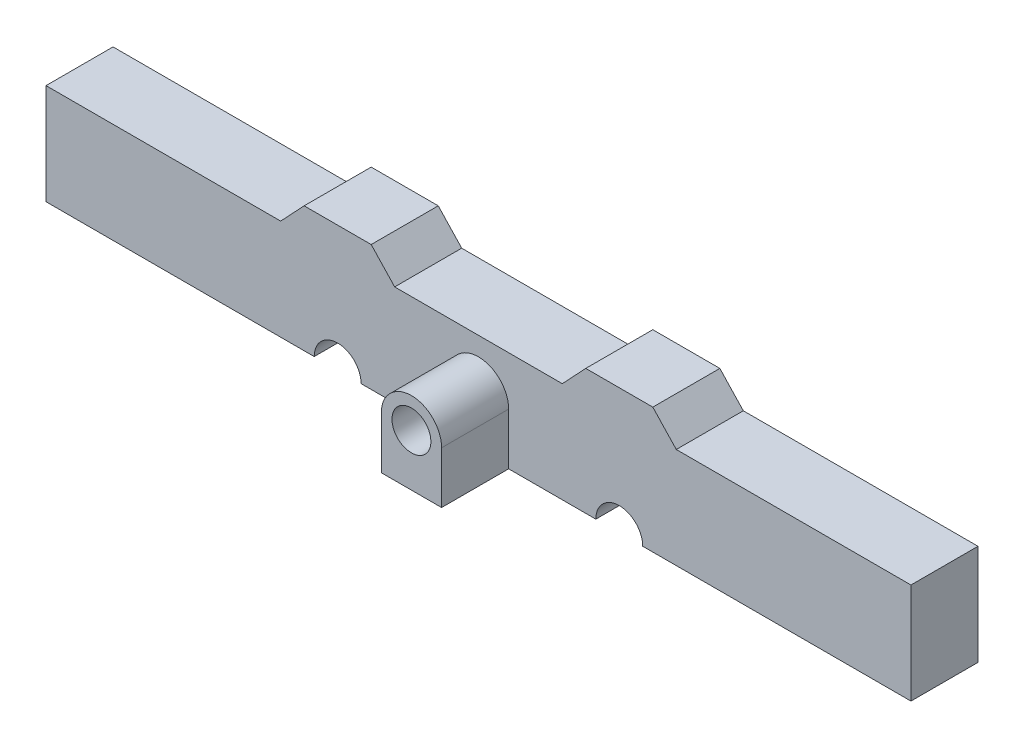
SolidWorks part; units mm, degrees
ref_plane "Front" through (0, 0, 0) normal (0, 0, 1) x (1, 0, 0)
ref_plane "Top" through (0, 0, 0) normal (0, 1, 0) x (1, 0, 0)
ref_plane "Right" through (0, 0, 0) normal (1, 0, 0) x (0, 0, -1)
sketch "Sketch1" plane through (0, 0, 0) normal (0, 0, 1) x (1, 0, 0)
  line L0 (0, 0) -> (0, 15)
  line L1 (0, 15) -> (35, 15)
  line L2 (0, 0) -> (40, 0)
  line L3 (47, 0) -> (82, 0)
  line L4 (43.5, 0) -> (43.5, 49.0227) construction
  line L5 (35, 15) -> (38.5, 18.7242)
  line L6 (38.5, 18.7242) -> (48.5, 18.7242)
  line L7 (52, 15) -> (48.5, 18.7242)
  line L8 (80.5, 18.7238) -> (77.0007, 15)
  line L9 (85.5, -4.9161) -> (85.5, 29.3767) construction
  line L10 (52, 15) -> (52, 49.0227) construction
  line L11 (52, 49.0227) -> (52, -10.3312) construction
  line L12 (77.0007, 15) -> (52, 15)
  line L13 (80.5, 18.7238) -> (85.5, 18.7238)
  line L14 (90.5, 18.7238) -> (85.5, 18.7238)
  line L15 (90.5, 18.7238) -> (93.9993, 15)
  line L16 (89, 0) -> (129, 0)
  line L17 (129, 0) -> (129, 15)
  line L18 (129, 15) -> (93.9993, 15)
  line L19 (2, 13) -> (35.865, 13)
  line L20 (35.865, 13) -> (39.365, 16.7242)
  line L21 (39.365, 16.7242) -> (47.635, 16.7242)
  line L22 (51.135, 13) -> (47.635, 16.7242)
  line L23 (77.8657, 13) -> (51.135, 13)
  line L24 (81.3651, 16.7238) -> (77.8657, 13)
  line L25 (81.3651, 16.7238) -> (85.5, 16.7238)
  line L26 (89.6349, 16.7238) -> (85.5, 16.7238)
  line L27 (89.6349, 16.7238) -> (93.1343, 13)
  line L28 (127, 13) -> (93.1343, 13)
  line L29 (127, 2) -> (127, 13)
  line L30 (90.6235, 2) -> (127, 2)
  line L31 (48.6235, 2) -> (80.3765, 2)
  line L32 (2, 2) -> (38.3765, 2)
  line L33 (2, 2) -> (2, 13)
  arc A0 (40, 0) -> (47, 0) centre (43.5, 0) cw
  arc A1 (82, 0) -> (89, 0) centre (85.5, 0) cw
  arc A2 (80.3765, 2) -> (90.6235, 2) centre (85.5, 0) cw
  arc A3 (38.3765, 2) -> (48.6235, 2) centre (43.5, 0) cw
  point P13 (43.5, 18.7242)
  point P22 (85.5, 13.5903)
  point P25 (85.5, 13.9843)
  dimension "D3" = 3.5
  dimension "D4" = 15
  dimension "D5" = 3.5
  dimension "D1" = 40
  dimension "D2" = 35
  dimension "D6" = 42
  dimension "D7" = 10
  dimension "D8" = 5
  dimension "D9" = 40
  dimension "D11" = 133.22
  dimension "D10" = 133.222
  dimension "D12" = 5.11
  dimension "D13" = 2
extrude "Boss-Extrude1" add sketch "Sketch1" along normal blind 10
sketch "Sketch2" plane through (0, 0, 10) normal (0, 0, 1) x (1, 0, 0)
  line L14 (0, 0) -> (40, 0)
  line L15 (47, 0) -> (82, 0)
  line L16 (89, 0) -> (129, 0)
  line L17 (129, 0) -> (129, 15)
  line L18 (129, 0) -> (129, 15)
  line L19 (129, 15) -> (93.9993, 15)
  line L20 (129, 15) -> (93.9993, 15)
  line L21 (93.9993, 15) -> (90.5, 18.7238)
  line L22 (93.9993, 15) -> (90.5, 18.7238)
  line L23 (52, 15) -> (48.5, 18.7242)
  line L24 (48.5, 18.7242) -> (38.5, 18.7242)
  line L25 (38.5, 18.7242) -> (35, 15)
  line L26 (35, 15) -> (0, 15)
  line L27 (0, 15) -> (0, 0)
  line L28 (0, 0) -> (40, 0)
  line L29 (47, 0) -> (82, 0)
  line L30 (89, 0) -> (129, 0)
  line L31 (90.5, 18.7238) -> (80.5, 18.7238)
  line L32 (90.5, 18.7238) -> (80.5, 18.7238)
  line L33 (80.5, 18.7238) -> (77.0007, 15)
  line L34 (80.5, 18.7238) -> (77.0007, 15)
  line L35 (77.0007, 15) -> (52, 15)
  line L36 (77.0007, 15) -> (52, 15)
  line L37 (52, 15) -> (48.5, 18.7242)
  line L38 (48.5, 18.7242) -> (38.5, 18.7242)
  line L39 (38.5, 18.7242) -> (35, 15)
  line L40 (35, 15) -> (0, 15)
  line L41 (0, 15) -> (0, 0)
  arc A2 (47, 0) -> (40, 0) centre (43.5, 0) ccw
  arc A3 (89, 0) -> (82, 0) centre (85.5, 0) ccw
  arc A4 (47, 0) -> (40, 0) centre (43.5, 0) ccw
  arc A5 (89, 0) -> (82, 0) centre (85.5, 0) ccw
  dimension "D1" = 0
extrude "Boss-Extrude2" add sketch "Sketch2" against normal blind 2
sketch "Sketch3" plane through (0, 0, 0) normal (0, 0, -1) x (-1, 0, 0)
  line L14 (-40, 0) -> (0, 0)
  line L15 (0, 0) -> (0, 15)
  line L16 (0, 15) -> (-35, 15)
  line L17 (-35, 15) -> (-38.5, 18.7242)
  line L18 (-38.5, 18.7242) -> (-48.5, 18.7242)
  line L19 (-48.5, 18.7242) -> (-52, 15)
  line L20 (-52, 15) -> (-77.0007, 15)
  line L21 (-52, 15) -> (-77.0007, 15)
  line L22 (-77.0007, 15) -> (-80.5, 18.7238)
  line L23 (-77.0007, 15) -> (-80.5, 18.7238)
  line L24 (-80.5, 18.7238) -> (-90.5, 18.7238)
  line L25 (-80.5, 18.7238) -> (-90.5, 18.7238)
  line L26 (-129, 0) -> (-89, 0)
  line L27 (-82, 0) -> (-47, 0)
  line L28 (-40, 0) -> (0, 0)
  line L29 (0, 0) -> (0, 15)
  line L30 (0, 15) -> (-35, 15)
  line L31 (-35, 15) -> (-38.5, 18.7242)
  line L32 (-38.5, 18.7242) -> (-48.5, 18.7242)
  line L33 (-48.5, 18.7242) -> (-52, 15)
  line L34 (-90.5, 18.7238) -> (-93.9993, 15)
  line L35 (-90.5, 18.7238) -> (-93.9993, 15)
  line L36 (-93.9993, 15) -> (-129, 15)
  line L37 (-93.9993, 15) -> (-129, 15)
  line L38 (-129, 15) -> (-129, 0)
  line L39 (-129, 15) -> (-129, 0)
  line L40 (-129, 0) -> (-89, 0)
  line L41 (-82, 0) -> (-47, 0)
  arc A2 (-82, 0) -> (-89, 0) centre (-85.5, 0) ccw
  arc A3 (-40, 0) -> (-47, 0) centre (-43.5, 0) ccw
  arc A4 (-82, 0) -> (-89, 0) centre (-85.5, 0) ccw
  arc A5 (-40, 0) -> (-47, 0) centre (-43.5, 0) ccw
  dimension "D1" = 0
extrude "Boss-Extrude3" add sketch "Sketch3" against normal blind 2
sketch "Sketch6" plane through (0, 0, 10) normal (0, 0, 1) x (1, 0, 0)
  circle A0 centre (64.5003, 7.7173) radius 4.5
  circle A1 centre (64.5003, 7.7173) radius 2.9
  dimension "D1" = 5.8
  dimension "D2" = 9
extrude "Boss-Extrude4" add sketch "Sketch6" along normal blind 10
sketch "Sketch7" plane through (0, 0, 10) normal (0, 0, 1) x (1, 0, 0)
  circle A0 centre (64.5003, 7.7173) radius 2.9
extrude "Cut-Extrude1" cut sketch "Sketch7" against normal blind 8
sketch "Sketch9" plane through (0, 0, 10) normal (0, 0, 1) x (1, 0, 0)
  line L0 (129, 15) -> (93.9993, 15) construction
  line L1 (64.5003, 7.7173) -> (64.5003, 46.1216) construction
  line L2 (129, 0) -> (129, 15) construction
  line L3 (64.5003, 46.1216) -> (64.5003, -9.2458) construction
  circle A0 centre (119, 7.5) radius 2.5
  circle A1 centre (103, 7.5) radius 2.5
  circle A2 centre (76.5003, 7.5) radius 2.5
  circle A3 centre (64.5003, 7.7173) radius 2.9 construction
  circle A4 centre (10.0007, 7.5) radius 2.5
  circle A5 centre (26.0007, 7.5) radius 2.5
  circle A6 centre (52.5003, 7.5) radius 2.5
  dimension "D1" = 5
  dimension "D2" = 7.5
  dimension "D4" = 5
  dimension "D5" = 5
  dimension "D6" = 12
  dimension "D3" = 10
extrude "Boss-Extrude5" add sketch "Sketch9" against normal up to surface (10 mm away) up to face at (64.5, 10.7435, 0)
sketch "Sketch10" plane through (0, 0, 20) normal (0, 0, 1) x (1, 0, 0)
  line L0 (60.0003, 7.7173) -> (60.0003, 0)
  line L1 (47, 0) -> (82, 0) construction
  line L2 (60.0003, 0) -> (69.0003, 0)
  line L3 (69.0003, 0) -> (69.0003, 7.7173)
  arc A0 (60.0003, 7.7173) -> (69.0003, 7.7173) centre (64.5003, 7.7173) ccw
  circle A1 centre (64.5003, 7.7173) radius 4.5 construction
extrude "Boss-Extrude6" add sketch "Sketch10" against normal up to surface (10 mm away) up to face at (64.5, 10.7435, 10)
